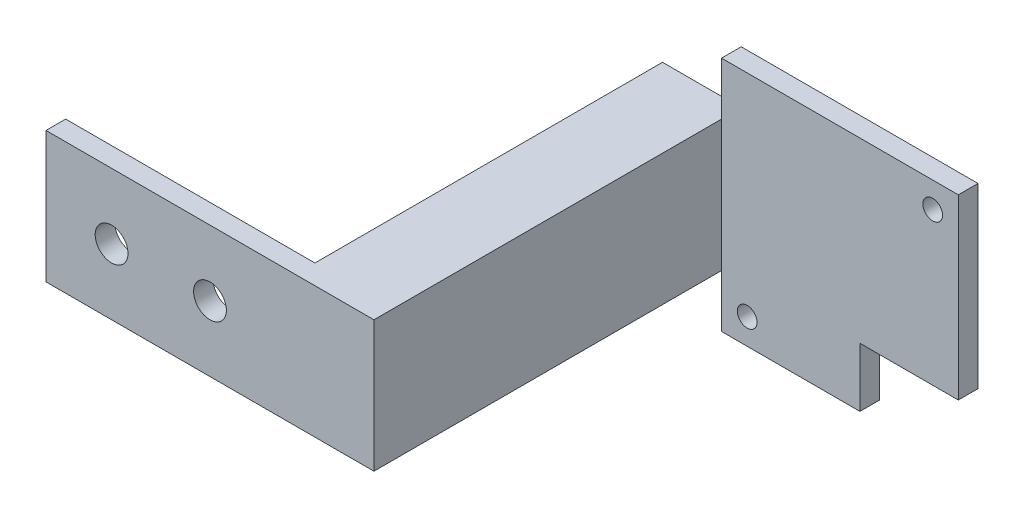
SolidWorks part; units mm, degrees
ref_plane "前视基准面" through (0, 0, 0) normal (0, 0, 1) x (1, 0, 0)
ref_plane "上视基准面" through (0, 0, 0) normal (0, 1, 0) x (1, 0, 0)
ref_plane "右视基准面" through (0, 0, 0) normal (1, 0, 0) x (0, 0, -1)
sketch "草图1" plane through (0, 0, 0) normal (0, 0, 1) x (1, 0, 0)
  line L1 (18.05, -18.05) -> (-18.05, -18.05)
  line L2 (18.05, -18.05) -> (18.05, 18.05)
  line L3 (18.05, 18.05) -> (-18.05, 18.05)
  line L4 (-18.05, -18.05) -> (-18.05, 18.05)
  line L5 (18.05, -18.05) -> (-18.05, 18.05) construction
  line L6 (18.05, 18.05) -> (-18.05, -18.05) construction
  point P0 (0, 0)
  dimension "D1" = 36.1
  dimension "D2" = 36.1
extrude "凸台-拉伸1" add sketch "草图1" along normal blind 3
sketch "草图2" plane through (0, 0, 3) normal (0, 0, 1) x (1, 0, 0)
  line L0 (0, 0) -> (14.1421, 14.1421) construction
  line L1 (0, 0) -> (18.05, -18.05) construction
  circle A0 centre (14.1421, 14.1421) radius 1.5
  circle A1 centre (-14.1421, -14.1421) radius 1.5
  dimension "D1" = 3
  dimension "D2" = 20
extrude "切除-拉伸1" cut sketch "草图2" against normal blind 3
sketch "草图3" plane through (0, 0, 3) normal (0, 0, 1) x (1, 0, 0)
  line L1 (18.05, -18.05) -> (3.05, -18.05)
  line L2 (18.05, -18.05) -> (18.05, -9.05)
  line L3 (18.05, -9.05) -> (3.05, -9.05)
  line L4 (3.05, -18.05) -> (3.05, -9.05)
  dimension "D1" = 15
  dimension "D2" = 9
extrude "切除-拉伸2" cut sketch "草图3" against normal blind 3
sketch "草图4" plane through (0, 0, 3) normal (0, 0, 1) x (1, 0, 0)
  line L0 (-18.05, 10) -> (-18.05, -10)
  line L1 (-18.05, 18.05) -> (-18.05, -18.05) construction
  line L2 (-18.05, -10) -> (-30.05, -10)
  line L3 (-30.05, -10) -> (-30.05, 10)
  line L4 (-30.05, 0) -> (-18.05, 0)
  line L5 (-18.05, 10) -> (-30.05, 10)
  line M7 (-18.05, 18.05) -> (-18.05, -18.05)
  dimension "D1" = 10
  dimension "D2" = 12
extrude "凸台-拉伸2" add sketch "草图4" against normal blind 3 contours L5 L3 L4 M7 | L4 L3 L2 L0
sketch "草图5" plane through (0, 0, 3) normal (0, 0, 1) x (1, 0, 0)
  line L1 (-18.05, -10) -> (-30.05, -10)
  line L2 (-18.05, -10) -> (-18.05, 10)
  line L3 (-18.05, 10) -> (-30.05, 10)
  line L4 (-30.05, -10) -> (-30.05, 10)
extrude "凸台-拉伸3" add sketch "草图5" along normal blind 50
sketch "草图7" plane through (0, 0, 53) normal (0, 0, 1) x (1, 0, 0)
  line L0 (-18.05, 10) -> (-30.05, 10) construction
  line L1 (-18.05, -10) -> (-68.05, -10)
  line L2 (-18.05, -10) -> (-18.05, 10)
  line L3 (-18.05, 10) -> (-68.05, 10)
  line L4 (-68.05, -10) -> (-68.05, 10)
  dimension "D1" = 50
extrude "凸台-拉伸4" add sketch "草图7" along normal blind 3
sketch "草图9" plane through (0, 0, 56) normal (0, 0, 1) x (1, 0, 0)
  line L0 (-68.05, 10) -> (-68.05, -10) construction
  circle A0 centre (-58.05, 0) radius 2.5
  circle A1 centre (-43.05, 0) radius 2.5
  dimension "D1" = 10
  dimension "D2" = 15
  dimension "D3" = 5
  dimension "D4" = 5
extrude "切除-拉伸4" cut sketch "草图9" against normal blind 3
